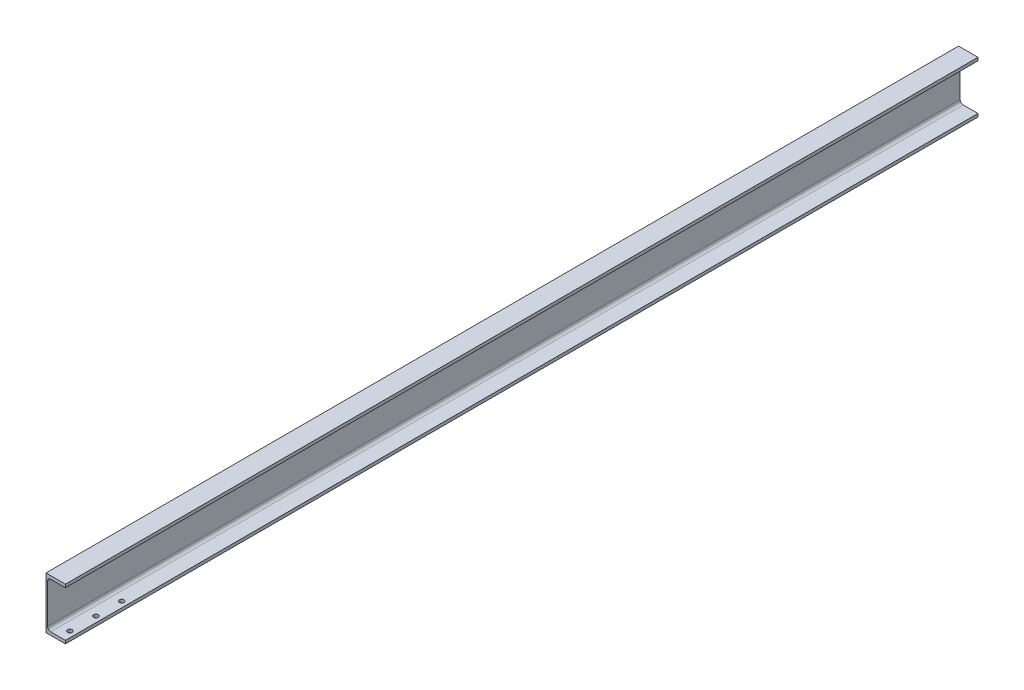
SolidWorks part; units mm, degrees
material "Plain Carbon Steel"
ref_plane "Front Plane" through (0, 0, 0) normal (0, 0, 1) x (1, 0, 0)
ref_plane "Top Plane" through (0, 0, 0) normal (0, 1, 0) x (1, 0, 0)
ref_plane "Right Plane" through (0, 0, 0) normal (1, 0, 0) x (0, 0, -1)
sketch "Sketch1" plane through (0, 0, 0) normal (0, 0, 1) x (1, 0, 0)
  line L0 (0, 100) -> (0, -100)
  line L1 (0, -100) -> (75, -100)
  line L2 (75, -100) -> (75, -88)
  line L3 (75, -88) -> (18, -88)
  line L4 (6, -76) -> (6, 76)
  line L5 (-29.6683, 0) -> (38.2219, 0) construction
  line L6 (75, 88) -> (18, 88)
  line L7 (75, 100) -> (75, 88)
  line L8 (0, 100) -> (75, 100)
  arc A0 (18, -88) -> (6, -76) centre (18, -76) cw
  arc A1 (18, 88) -> (6, 76) centre (18, 76) ccw
  point P13 (6, 0)
  point P16 (0, 0)
  dimension "D1" = 6
  dimension "D3" = 75
  dimension "D5" = 12
  dimension "D2" = 12
  dimension "D4" = 100
extrude "Boss-Extrude1" add sketch "Sketch1" along normal mid plane 3525
sketch "Sketch2" plane through (0, -100, 0) normal (0, -1, 0) x (1, 0, 0)
  line L0 (0, 1762.5) -> (75, 1762.5) construction
  line L1 (75, 1762.5) -> (75, -1762.5) construction
  circle A0 centre (52.5, 1722.5) radius 9
  circle A1 centre (52.5, 1622.5) radius 9
  circle A3 centre (52.5, 1522.5) radius 9
  dimension "D1" = 18
  dimension "D2" = 18
  dimension "D3" = 100
  dimension "D4" = 18
  dimension "D5" = 100
  dimension "D6" = 40
  dimension "D7" = 22.5
  dimension "D8" = 22.5
  dimension "D9" = 22.5
extrude "Cut-Extrude1" cut sketch "Sketch2" against normal up to next
